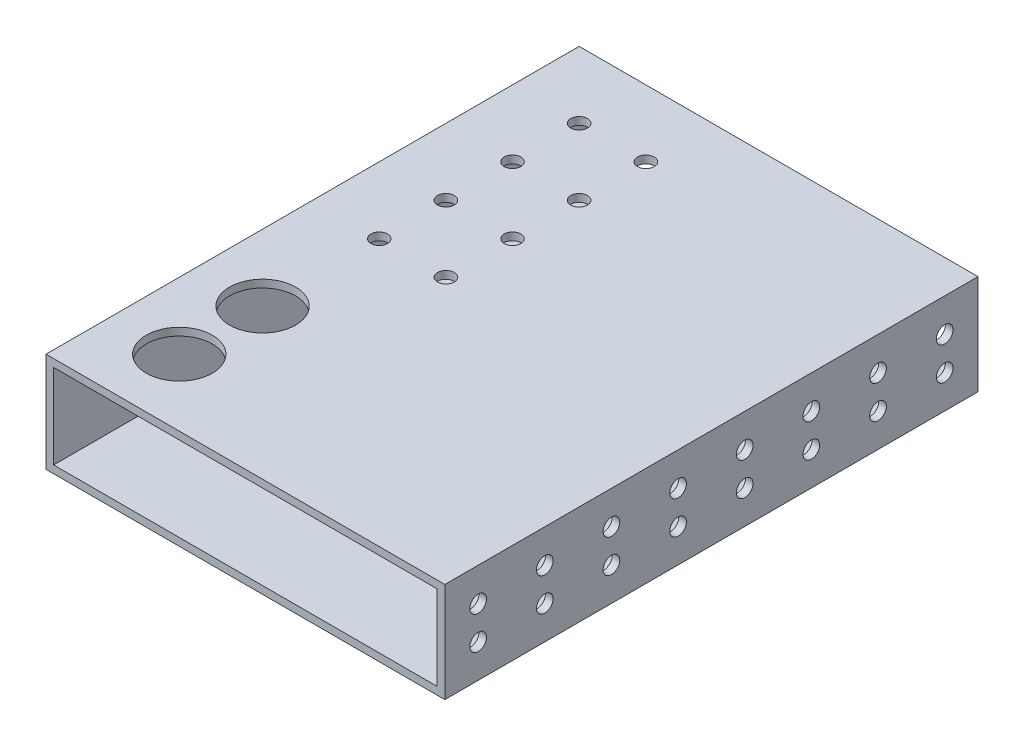
SolidWorks part; units mm, degrees
material "6063-T1"
ref_plane "Front Plane" through (0, 0, 0) normal (0, 0, 1) x (1, 0, 0)
ref_plane "Top Plane" through (0, 0, 0) normal (0, 1, 0) x (1, 0, 0)
ref_plane "Right Plane" through (0, 0, 0) normal (1, 0, 0) x (0, 0, -1)
sketch "Sketch1" plane through (0, 0, 0) normal (0, 0, 1) x (1, 0, 0)
  line L0 (-73.0898, 16.0947) -> (-73.0898, 19.0081) construction
  line L1 (-76.0032, -19.0081) -> (76.0031, -19.0081)
  line L2 (-76.0032, -19.0081) -> (-76.0032, 19.0081)
  line L3 (-76.0032, 19.0081) -> (76.0031, 19.0081)
  line L4 (76.0031, -19.0081) -> (76.0031, 19.0081)
  line L5 (-76.0032, -19.0081) -> (76.0031, 19.0081) construction
  line L6 (-76.0032, 19.0081) -> (76.0031, -19.0081) construction
  line L7 (-73.0898, 16.0947) -> (73.0898, 16.0947)
  line L8 (-73.0898, 16.0947) -> (-73.0898, -16.0947)
  line L9 (-73.0898, -16.0947) -> (73.0898, -16.0947)
  line L10 (73.0898, 16.0947) -> (73.0898, -16.0947)
  line L11 (-73.0898, 16.0947) -> (73.0898, -16.0947) construction
  line L12 (-73.0898, -16.0947) -> (73.0898, 16.0947) construction
  line L13 (-73.0898, 16.0947) -> (-76.0032, 16.0947) construction
  point P0 (0, 0)
  point P6 (0, 0)
  dimension "D1" = 38.0162
  dimension "D2" = 152.0063
  dimension "D3" = 2.9134
extrude "Boss-Extrude1" add sketch "Sketch1" along normal mid plane 203.2 contours L3 L4 L1 L2
sketch "Sketch2"
  line L0 (-50.6032, -101.6) -> (-50.6032, 49898.4) construction
  line L2 (-25.2032, -101.6) -> (-25.2032, 49898.4) construction
  line L5 (-76.0032, -101.6) -> (-76.0032, 101.6) construction
  line L6 (-50.6032, 76.2) -> (49949.3968, 76.2) construction
  line L8 (76.0031, 101.6) -> (-76.0032, 101.6) construction
  circle A0 centre (-50.6032, -76.2) radius 12.5789
  circle A1 centre (-50.6032, -44.45) radius 12.5789
  circle A3 centre (-50.6032, 76.2) radius 3.175
  circle A4 centre (-50.6032, 50.8) radius 3.175
  circle A5 centre (-50.6032, 25.4) radius 3.175
  circle A6 centre (-50.6032, 0) radius 3.175
  circle A7 centre (-25.2032, 76.2) radius 3.175
  circle A8 centre (-25.2032, 50.8) radius 3.175
  circle A9 centre (-25.2032, 25.4) radius 3.175
  circle A10 centre (-25.2032, 0) radius 3.175
other "AlignGroup1"
other "AlignGroup2" parameters "D1"=30.0238, "D2"=21.0577, "D3"=31.5865, "D4"=23.4874, "D5"=76.2, "D6"=43.3749, "D7"=203.2, "D8"=0.6126, "D9"=21.6124, "D10"=26.1583, "D11"=26.1583, "D12"=57.9083
other "AlignGroup3"
other "AlignGroup4"
extrude "Cut-Extrude1" cut sketch "Sketch2" against normal up to surface (2.9134 mm away)
sketch "Sketch3" plane through (76.0031, 0, 0) normal (1, 0, 0) x (0, 0, -1)
  line L0 (-74.1621, 6.3081) -> (49925.8379, 6.3081) construction
  line L1 (-88.3478, -6.3081) -> (49911.6522, -6.3081) construction
  line L2 (-101.6, 19.0081) -> (101.6, 19.0081) construction
  line L3 (-101.6, -19.0081) -> (101.6, -19.0081) construction
  line L4 (-101.6, -19.0081) -> (-101.6, 19.0081) construction
  line L5 (-88.9, 6.3081) -> (-88.9, -49993.6919) construction
  line L6 (-63.5, 4.7307) -> (-63.5, -49995.2693) construction
  line L7 (-38.1, 6.3081) -> (-38.1, -49993.6919) construction
  line L8 (-12.7, 6.3081) -> (-12.7, -49993.6919) construction
  line L9 (12.7, 6.3081) -> (12.7, -49993.6919) construction
  line L10 (38.1, 6.3081) -> (38.1, -49993.6919) construction
  line L11 (63.5, 6.3081) -> (63.5, -49993.6919) construction
  line L12 (88.9, 6.3081) -> (88.9, -49993.6919) construction
  circle A0 centre (63.5, 6.3081) radius 3.175
  circle A1 centre (38.1, 6.3081) radius 3.175
  circle A2 centre (12.7, 6.3081) radius 3.175
  circle A3 centre (-12.7, 6.3081) radius 3.175
  circle A4 centre (63.5, -6.3081) radius 3.175
  circle A5 centre (38.1, -6.3081) radius 3.175
  circle A6 centre (12.7, -6.3081) radius 3.175
  circle A7 centre (-12.7, -6.3081) radius 3.175
  circle A8 centre (-38.1, 6.3081) radius 3.175
  circle A9 centre (-38.1, -6.3081) radius 3.175
  circle A10 centre (-63.5, 6.3081) radius 3.175
  circle A11 centre (-63.5, -6.3081) radius 3.175
  circle A12 centre (-88.9, 6.3081) radius 3.175
  circle A13 centre (-88.9, -6.3081) radius 3.175
  circle A14 centre (88.9, 6.3081) radius 3.175
  circle A15 centre (88.9, -6.3081) radius 3.175
  point P41 (91.8278, -6.3081)
other "AlignGroup5"
other "AlignGroup6" parameters "D12"=12.51, "D1"=10.3457, "D2"=10.3556, "D3"=0, "D4"=12.7, "D5"=38.1, "D6"=63.5, "D7"=88.9, "D8"=114.3, "D9"=139.7, "D10"=165.1, "D11"=203.2
extrude "Cut-Extrude2" cut sketch "Sketch3" against normal up to surface (2.9134 mm away) contours A3 | A2 | A1 | A0 | A14 | A15 | A4 | A5 | A6 | A7 | A9 | A11 | A13 | A12 | A10 | A8 up to face at (73.0898, 0, 0)
equation "\"length\"= 8in"
equation "\"channels\"= 8"
equation "\"post_spacing\"= \"length\" / ( \"channels\" + 1 )"
equation "\"base_post_spacing\"= 0"
